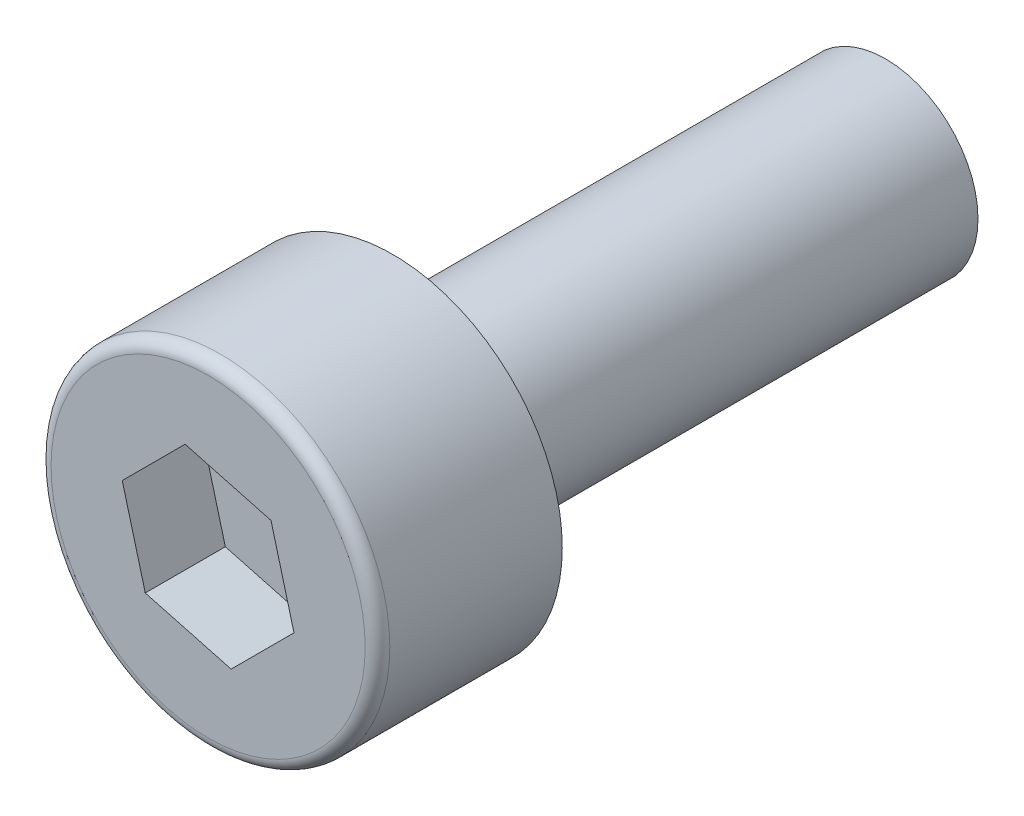
SolidWorks part; units mm, degrees
ref_plane "前视基准面" through (0, 0, 0) normal (0, 0, 1) x (1, 0, 0)
ref_plane "上视基准面" through (0, 0, 0) normal (0, 1, 0) x (1, 0, 0)
ref_plane "右视基准面" through (0, 0, 0) normal (1, 0, 0) x (0, 0, -1)
sketch "草图1" plane through (0, 0, 0) normal (0, 0, 1) x (1, 0, 0)
  circle A0 centre (0, 0) radius 2.75
  dimension "D1" = 5.5
extrude "凸台-拉伸1" add sketch "草图1" along normal blind 3
sketch "草图2" plane through (0, 0, 3) normal (0, 0, 1) x (1, 0, 0)
  line L1 (-1.0206, -1.0206) -> (0.3736, -1.3942)
  line L2 (0.3736, -1.3942) -> (1.3942, -0.3736)
  line L3 (1.3942, -0.3736) -> (1.0206, 1.0206)
  line L4 (1.0206, 1.0206) -> (-0.3736, 1.3942)
  line L5 (-0.3736, 1.3942) -> (-1.3942, 0.3736)
  line L6 (-1.3942, 0.3736) -> (-1.0206, -1.0206)
  circle A0 centre (0, 0) radius 1.25 construction
  dimension "D1" = 2.5
extrude "切除-拉伸1" cut sketch "草图2" against normal blind 1.3
sketch "草图3" plane through (0, 0, 0) normal (0, 0, -1) x (-1, 0, 0)
  circle A0 centre (0, 0) radius 1.5
  dimension "D1" = 3
extrude "凸台-拉伸2" add sketch "草图3" along normal blind 8
fillet "圆角1" radius 0.2 1 edges at (2.75, 0, 3)
